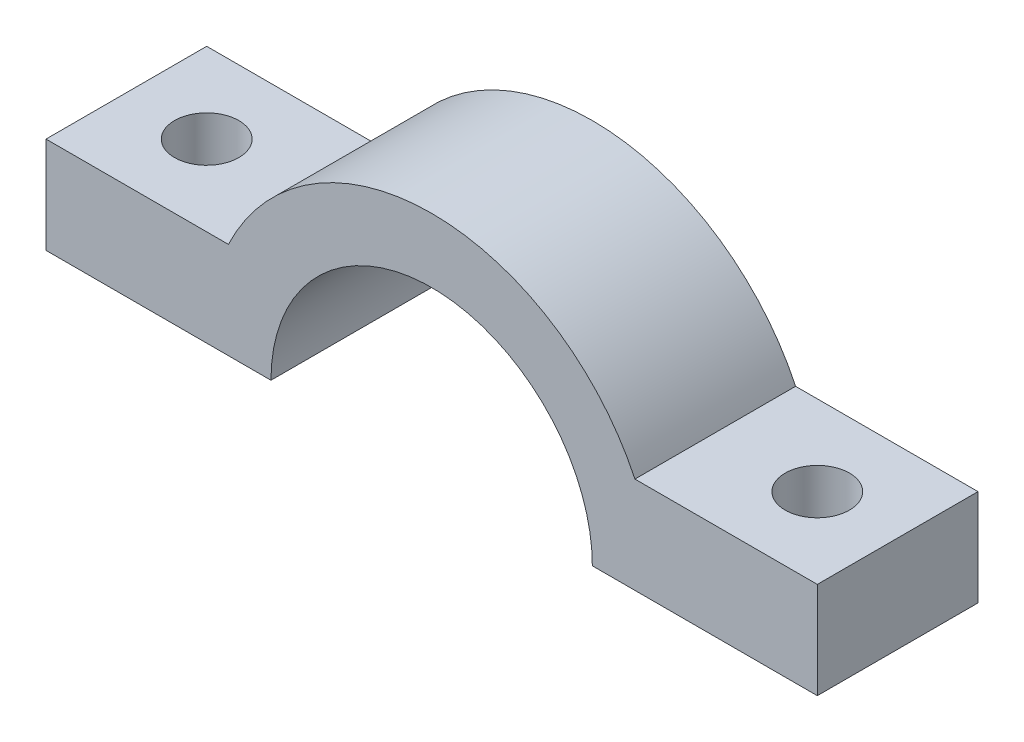
SolidWorks part; units mm, degrees
ref_plane "Front Plane" through (0, 0, 0) normal (0, 0, 1) x (1, 0, 0)
ref_plane "Top Plane" through (0, 0, 0) normal (0, 1, 0) x (1, 0, 0)
ref_plane "Right Plane" through (0, 0, 0) normal (1, 0, 0) x (0, 0, -1)
sketch "Sketch1" plane through (0, 0, 0) normal (0, 0, 1) x (1, 0, 0)
  line L0 (-7, 0) -> (-5, 0)
  line L1 (5, 0) -> (7, 0)
  line L2 (-7, 0) -> (-12, 0)
  line L3 (-12, 0) -> (-12, 3)
  line L4 (-12, 3) -> (-6.3246, 3)
  line L5 (0, 0) -> (0, -4.8969) construction
  line L6 (12, 3) -> (6.3246, 3)
  line L7 (7, 0) -> (12, 0)
  line L8 (12, 0) -> (12, 3)
  arc A0 (5, 0) -> (-5, 0) centre (0, 0) ccw
  arc A1 (6.3246, 3) -> (-6.3246, 3) centre (0, 0) ccw
  dimension "D1" = 10
  dimension "D2" = 14
  dimension "D3" = 5
  dimension "D4" = 3
extrude "Boss-Extrude1" add sketch "Sketch1" along normal blind 5
sketch "Sketch2" plane through (0, 3, 0) normal (0, 1, 0) x (1, 0, 0)
  line L0 (-12, 0) -> (-9.5, 0) construction
  line L1 (0, 0) -> (0, -9.4325) construction
  line L2 (-6.3246, 0) -> (-12, 0) construction
  line L3 (-9.5, 0) -> (-9.5, -2.5) construction
  circle A0 centre (-9.5, -2.5) radius 1
  circle A1 centre (9.5, -2.5) radius 1
  dimension "D3" = 2
  dimension "D1" = 2.5
  dimension "D2" = 2.5
extrude "Cut-Extrude1" cut sketch "Sketch2" against normal blind 5
